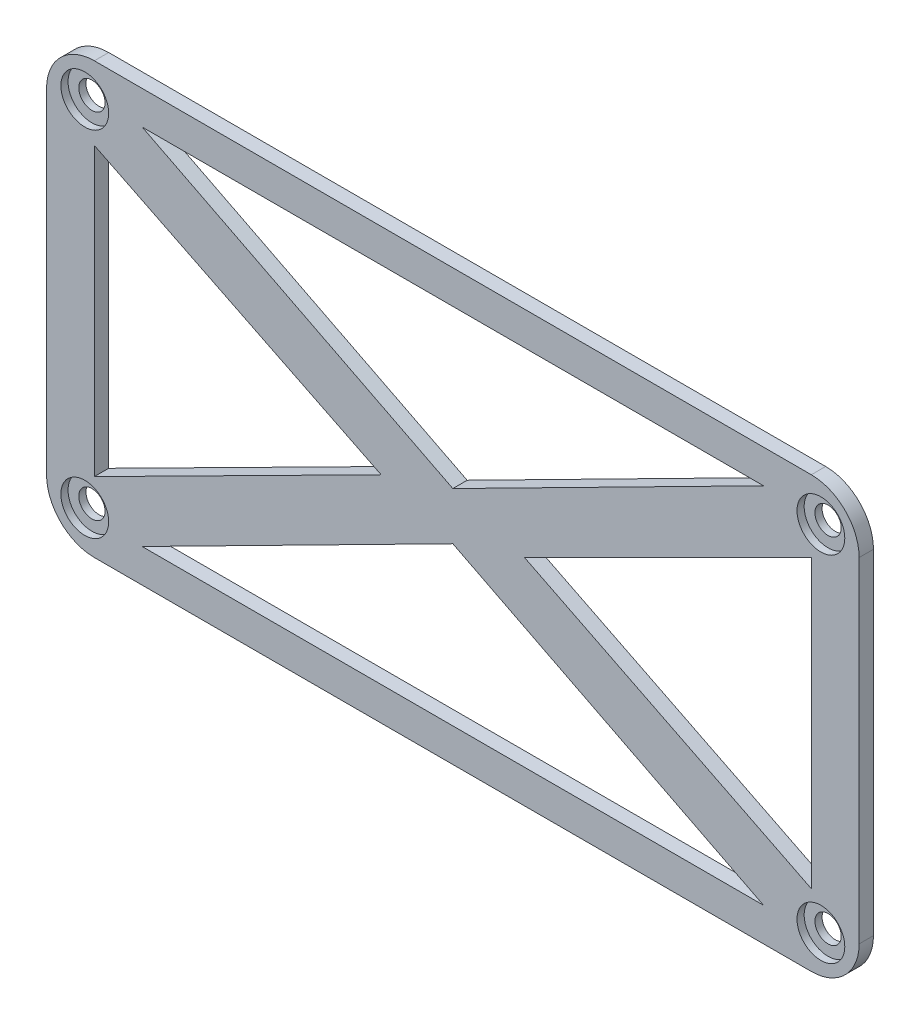
SolidWorks part; units mm, degrees
ref_plane "前视基准面" through (0, 0, 0) normal (0, 0, 1) x (1, 0, 0)
ref_plane "上视基准面" through (0, 0, 0) normal (0, 1, 0) x (1, 0, 0)
ref_plane "右视基准面" through (0, 0, 0) normal (1, 0, 0) x (0, 0, -1)
sketch "草图1" plane through (0, 0, 0) normal (0, 0, 1) x (1, 0, 0)
  line L1 (-72.5741, 45.4874) -> (77.4259, 45.4874)
  line L2 (-82.5741, 35.4874) -> (-82.5741, -34.5126)
  line L3 (-72.5741, -44.5126) -> (77.4259, -44.5126)
  line L4 (87.4259, 35.4874) -> (87.4259, -34.5126)
  arc A0 (-72.5741, 45.4874) -> (-82.5741, 35.4874) centre (-72.5741, 35.4874) ccw
  arc A1 (-72.5741, -44.5126) -> (-82.5741, -34.5126) centre (-72.5741, -34.5126) cw
  arc A2 (87.4259, 35.4874) -> (77.4259, 45.4874) centre (77.4259, 35.4874) ccw
  arc A3 (87.4259, -34.5126) -> (77.4259, -44.5126) centre (77.4259, -34.5126) cw
  dimension "D1" = 10
  dimension "D2" = 10
  dimension "D3" = 10
  dimension "D4" = 10
  dimension "D5" = 90
  dimension "D6" = 170
extrude "凸台-拉伸1" add sketch "草图1" along normal blind 3
ref_plane "for screw hole" through (0, 0, 3) normal (0, 0, 1) x (1, 0, 0)
sketch "草图2" plane through (0, 0, 3) normal (0, 0, 1) x (1, 0, 0)
  line L0 (77.4259, 45.4874) -> (-72.5741, 45.4874) construction
  line L1 (-82.5741, 35.4874) -> (-82.5741, -34.5126) construction
  line L2 (-72.5741, -44.5126) -> (77.4259, -44.5126) construction
  line L3 (87.4259, -34.5126) -> (87.4259, 35.4874) construction
  line L4 (-62.5741, 38.4874) -> (2.4259, 5.4874)
  line L6 (-72.5741, 30.1561) -> (-12.5741, 0.4874)
  line L8 (2.4259, -4.5126) -> (-62.5741, -37.5126)
  line L10 (67.4259, -37.5126) -> (2.4259, -4.5126)
  line L12 (-72.5741, -29.8439) -> (-12.5741, 0.4874)
  line L13 (-72.5741, 30.1561) -> (-72.5741, -29.8439)
  line L15 (-62.5741, -37.5126) -> (67.4259, -37.5126)
  line L17 (67.4259, 38.4874) -> (2.4259, 5.4874)
  line L19 (-62.5741, 38.4874) -> (67.4259, 38.4874)
  line L21 (17.4259, 0.4874) -> (77.4259, 30.4874)
  line L25 (17.4259, 0.4874) -> (77.4259, -29.5126)
  line L26 (77.4259, -29.5126) -> (77.4259, 30.4874)
  circle A0 centre (-74.5741, 37.4874) radius 2.75
  circle A1 centre (-74.5741, -36.5126) radius 2.75
  circle A2 centre (79.4259, 37.4874) radius 2.75
  circle A3 centre (79.4259, -36.5126) radius 2.75
  point P19 (-62.5741, 30.4874)
  point P23 (77.4259, 30.4874)
  point P38 (2.4259, 5.4874)
  point P39 (-12.5741, 0.4874)
  point P40 (67.4259, 38.4874)
  point P41 (-62.5741, 38.4874)
  point P42 (2.4259, -4.5126)
  point P43 (17.4259, 0.4874)
  point P45 (-72.5741, -29.8439)
  point P46 (-62.5741, -37.5126)
  point P47 (67.4259, -37.5126)
  point P48 (77.4259, -29.5126)
  dimension "D2" = 5.5
  dimension "D3" = 5.5
  dimension "D4" = 5.5
  dimension "D8" = 8
  dimension "D9" = 8
  dimension "D10" = 8
  dimension "D11" = 5.5
  dimension "D14" = 70
  dimension "D5" = 8
  dimension "D6" = 8
  dimension "D7" = 8
  dimension "D12" = 8
  dimension "D13" = 8
  dimension "D15" = 70
  dimension "D16" = 40
  dimension "D17" = 45
  dimension "D18" = 45
  dimension "D19" = 60
  dimension "D20" = 7
  dimension "D21" = 7
  dimension "D22" = 20
  dimension "D23" = 20
  dimension "D24" = 20
  dimension "D25" = 10
  dimension "D26" = 7
  dimension "D27" = 20
  dimension "D28" = 15
  dimension "D29" = 15
  dimension "D30" = 10
  dimension "D31" = 10
  dimension "D32" = 15
  dimension "D33" = 7
  dimension "D34" = 20
extrude "切除-拉伸1" cut sketch "草图2" against normal blind 10 and the other way blind 39
ref_plane "for outer screw hole" through (0, 0, 3) normal (0, 0, 1) x (1, 0, 0)
sketch "草图3" plane through (0, 0, 3) normal (0, 0, 1) x (1, 0, 0)
  circle A0 centre (-74.5741, 37.4874) radius 5
  circle A1 centre (79.4259, 37.4874) radius 5
  circle A2 centre (79.4259, -36.5126) radius 5
  circle A3 centre (-74.5741, -36.5126) radius 5
  dimension "D1" = 10
  dimension "D2" = 10
  dimension "D3" = 10
  dimension "D4" = 10
extrude "切除-拉伸2" cut sketch "草图3" against normal blind 1.5
ref_plane "for stands" through (0, 0, 3) normal (0, 0, 1) x (1, 0, 0)
